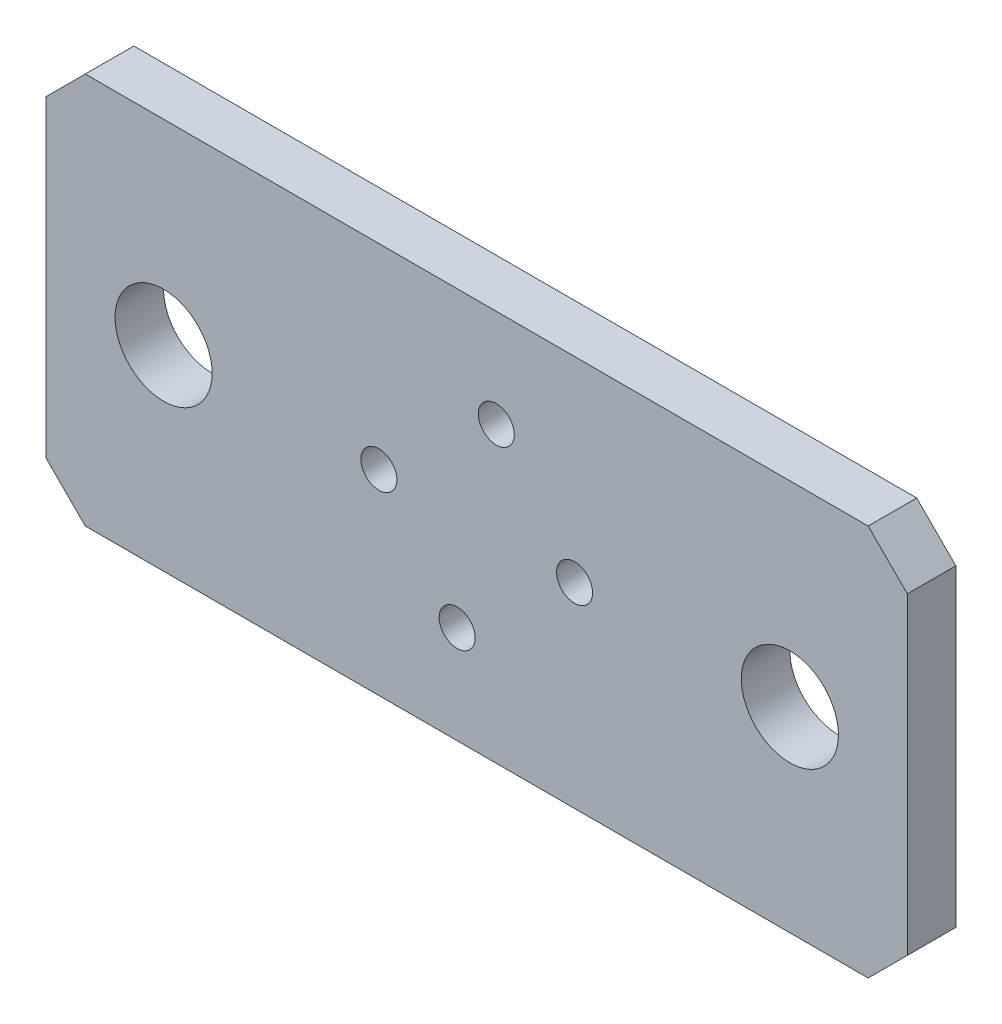
SolidWorks part; units mm, degrees
ref_plane "Front Plane" through (0, 0, 0) normal (0, 0, 1) x (1, 0, 0)
ref_plane "Top Plane" through (0, 0, 0) normal (0, 1, 0) x (1, 0, 0)
ref_plane "Right Plane" through (0, 0, 0) normal (1, 0, 0) x (0, 0, -1)
sketch "Model" plane through (0, 0, 0) normal (0, 0, 1) x (1, 0, 0)
  line L0 (0, 11.43) -> (1.27, 12.7)
  line L1 (27.94, 11.43) -> (27.94, 1.27)
  line L2 (27.94, 1.27) -> (26.67, 0)
  line L3 (0, 1.27) -> (0, 11.43)
  line L4 (1.27, 12.7) -> (26.67, 12.7)
  line L5 (26.67, 12.7) -> (27.94, 11.43)
  line L6 (1.27, 0) -> (0, 1.27)
  line L7 (26.67, 0) -> (1.27, 0)
  circle A0 centre (10.795, 6.35) radius 0.5842
  circle A1 centre (17.145, 6.35) radius 0.5842
  circle A2 centre (3.81, 6.35) radius 1.5748
  circle A3 centre (24.13, 6.35) radius 1.5748
  circle A4 centre (13.335, 3.175) radius 0.5842
  circle A5 centre (14.605, 9.525) radius 0.5842
extrude "Boss-Extrude1" add sketch "Model" along normal blind 1.5748
